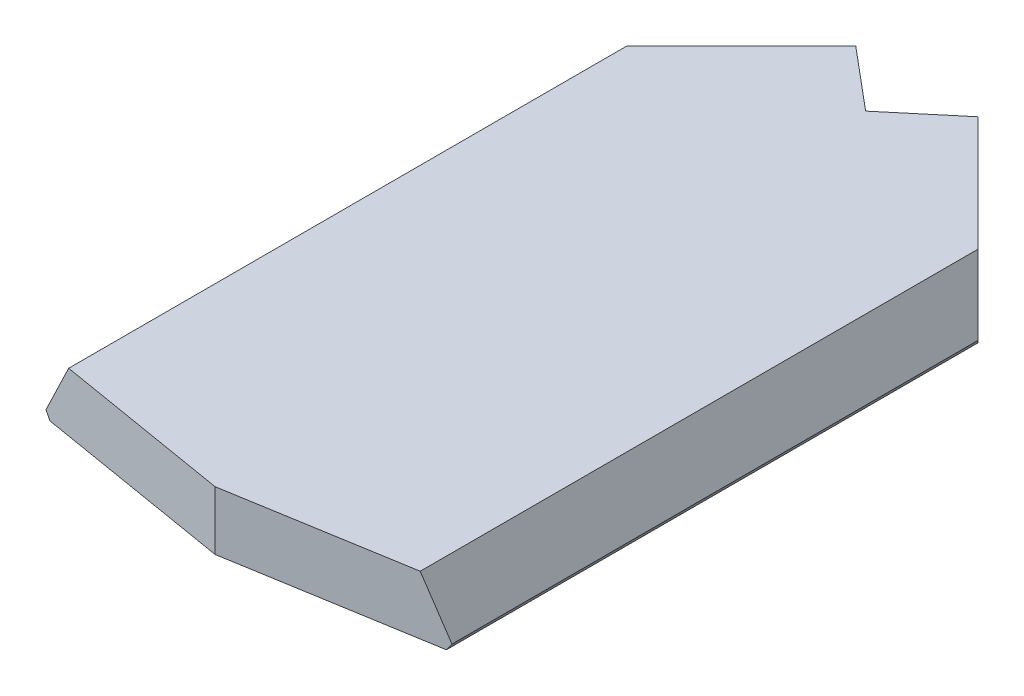
SolidWorks part; units mm, degrees
ref_plane "Front Plane" through (0, 0, 0) normal (0, 0, 1) x (1, 0, 0)
ref_plane "Top Plane" through (0, 0, 0) normal (0, 1, 0) x (1, 0, 0)
ref_plane "Right Plane" through (0, 0, 0) normal (1, 0, 0) x (0, 0, -1)
sketch "Sketch1" plane through (0, 0, 0) normal (0, 1, 0) x (1, 0, 0)
  line L0 (0, 39.6221) -> (0, 0) construction
  line L1 (-23.9488, 39.6221) -> (23.9488, 39.6221) construction
  line L2 (-23.9488, 39.6221) -> (-23.9488, -56) construction
  line L3 (-23.9488, -56) -> (23.9488, -56) construction
  line L4 (23.9488, 39.6221) -> (23.9488, -56) construction
  line L5 (0, 0) -> (23.9488, 0) construction
  line L6 (-23.9488, -52) -> (-23.9488, 24) construction
  line L7 (0, 0) -> (-23.9488, 0) construction
  line L8 (0, 0) -> (0, -56) construction
  line L9 (-23.9488, -52) -> (0, -56)
  line L10 (0, -56) -> (23.9488, -52)
  line L11 (23.9488, -52) -> (23.9488, 24)
  line L12 (23.9488, 24) -> (8.3267, 39.6221)
  line L13 (8.3267, 39.6221) -> (0, 32.6351)
  line L14 (0, 32.6351) -> (-8.3267, 39.6221)
  line L15 (-8.3267, 39.6221) -> (-23.9488, 24)
  line L16 (-23.9488, 24) -> (-23.9488, -52)
  line L17 (0, 32.6351) -> (-8.3267, 39.6221) construction
  line L18 (8.3267, 39.6221) -> (0, 32.6351) construction
  line L19 (23.9488, 24) -> (8.3267, 39.6221) construction
sketch "Sketch2" plane through (0, 0, 0) normal (0, 0, 1) x (1, 0, 0)
  line L0 (23.9488, 0) -> (27.6564, -7.054)
  line L1 (27.6564, -7.054) -> (27.0051, -8)
  line L2 (27.0051, -8) -> (-27.0051, -8)
  line L3 (-27.0051, -8) -> (-27.6564, -7.054)
  line L5 (-27.6564, -7.054) -> (-23.9488, 0)
  line L6 (-23.9488, 0) -> (23.9488, 0)
extrude "Boss-Extrude1" add sketch "Sketch2" along normal up to vertex (56 mm away) from vertex at -39.6221 starting at point (-8.3267, 0, -39.6221)
sketch "Sketch3" plane through (0, 0, 0) normal (0, 1, 0) x (1, 0, 0)
  line L0 (0, 32.6351) -> (8.3267, 39.6221)
  line L1 (8.3267, 39.6221) -> (27.6564, 20.2924)
  line L2 (27.6564, 20.2924) -> (27.6564, -51.3808)
  line L3 (27.6564, -51.3808) -> (0, -56)
  line L4 (0, -56) -> (-27.6564, -51.3808)
  line L5 (-27.6564, -51.3808) -> (-27.6564, 20.2924)
  line L6 (-27.6564, 20.2924) -> (-8.3267, 39.6221)
  line L7 (-8.3267, 39.6221) -> (0, 32.6351)
  line L8 (-8.3267, 39.6221) -> (-23.9488, 24) construction
  line L9 (23.9488, 24) -> (8.3267, 39.6221) construction
  line L10 (0, -56) -> (23.9488, -52) construction
  line L11 (-23.9488, -52) -> (0, -56) construction
  line L12 (0, -56) -> (0, 32.6351) construction
extrude "Cut-Extrude1" cut sketch "Sketch3" against normal through all flip side to cut
